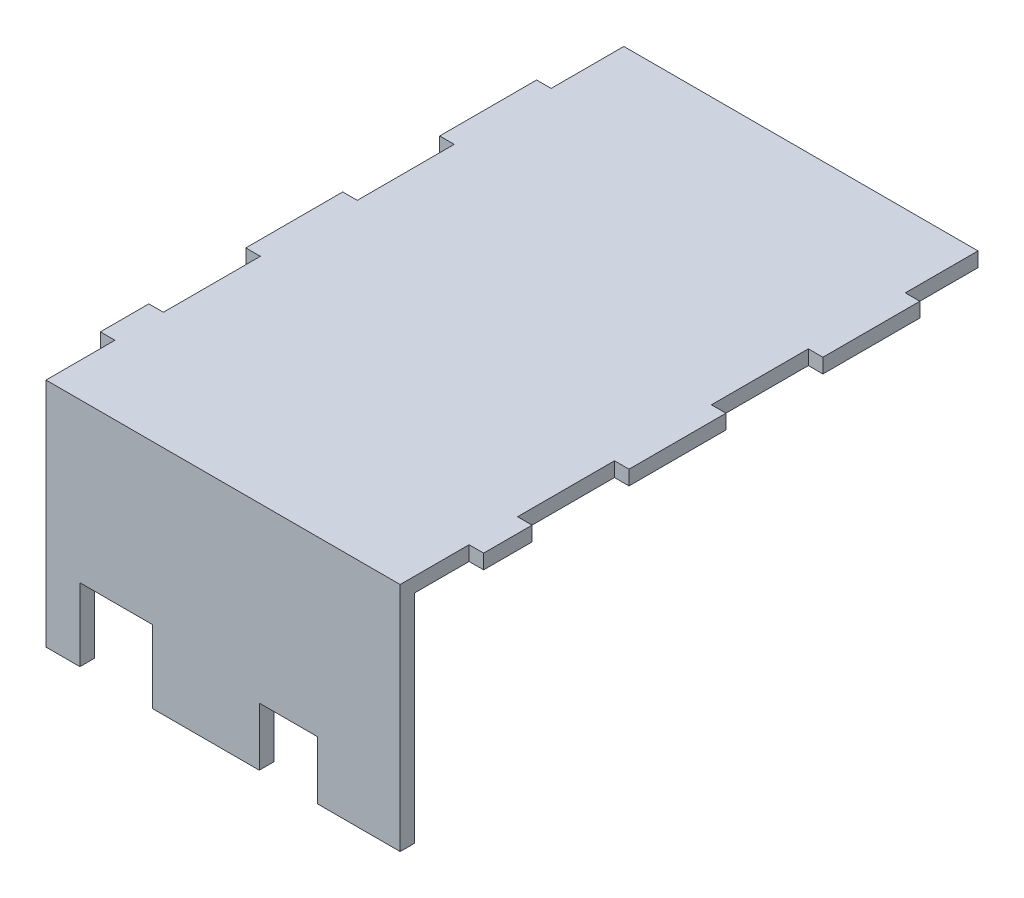
SolidWorks part; units mm, degrees
ref_plane "Front Plane" through (0, 0, 0) normal (0, 0, 1) x (1, 0, 0)
ref_plane "Top Plane" through (0, 0, 0) normal (0, 1, 0) x (1, 0, 0)
ref_plane "Right Plane" through (0, 0, 0) normal (1, 0, 0) x (0, 0, -1)
sketch "Croquis1" plane through (0, 0, 0) normal (0, 1, 0) x (1, 0, 0)
  line L0 (-44.0044, 25.1156) -> (29.0656, 25.1156)
  line L1 (29.0656, 25.1156) -> (29.0656, 10.1156)
  line L3 (-44.0044, -69.8844) -> (-44.0044, -49.8844)
  line L4 (-44.0044, 25.1156) -> (-44.0044, 10.1156)
  line L5 (-44.0044, 10.1156) -> (-47.0044, 10.1156)
  line L6 (-47.0044, 10.1156) -> (-47.0044, -9.8844)
  line L7 (-47.0044, -9.8844) -> (-44.0044, -9.8844)
  line L8 (-44.0044, -9.8844) -> (-44.0044, -29.8844)
  line L9 (-44.0044, -29.8844) -> (-47.0044, -29.8844)
  line L10 (-47.0044, -29.8844) -> (-47.0044, -49.8844)
  line L11 (-47.0044, -49.8844) -> (-44.0044, -49.8844)
  line L12 (-44.0044, -49.8844) -> (-44.0044, -69.8844)
  line L13 (-44.0044, -69.8844) -> (-47.0044, -69.8844)
  line L14 (-47.0044, -69.8844) -> (-47.0044, -79.8844)
  line L15 (-47.0044, -79.8844) -> (-44.0044, -79.8844)
  line L17 (-44.0044, -94.1044) -> (29.0656, -94.1044)
  line L18 (29.0656, -94.1044) -> (29.0656, -82.8844)
  line L19 (-44.0044, -79.8844) -> (-44.0044, -94.1044)
  line L20 (29.0656, -9.8844) -> (29.0656, -29.8844)
  line L21 (32.0656, -79.8844) -> (29.0656, -79.8844)
  line L22 (32.0656, -69.8844) -> (32.0656, -79.8844)
  line L23 (29.0656, -69.8844) -> (32.0656, -69.8844)
  line L24 (32.0656, -49.8844) -> (29.0656, -49.8844)
  line L25 (32.0656, -29.8844) -> (32.0656, -49.8844)
  line L26 (29.0656, -29.8844) -> (32.0656, -29.8844)
  line L27 (32.0656, -9.8844) -> (29.0656, -9.8844)
  line L28 (32.0656, 10.1156) -> (32.0656, -9.8844)
  line L29 (29.0656, 10.1156) -> (32.0656, 10.1156)
  line L30 (29.0656, -49.8844) -> (29.0656, -69.8844)
  line L31 (29.0656, -79.8844) -> (29.0656, -82.8844)
  line L32 (-44.0044, -29.8844) -> (-44.0044, -9.8844)
  line L33 (-44.0044, 10.1156) -> (-44.0044, 25.1156)
  point P3 (0, 0)
  dimension "D10" = 14.22
  dimension "D1" = 73.07
  dimension "D2" = 108
  dimension "D3" = 15
  dimension "D4" = 3
  dimension "D5" = 20
  dimension "D6" = 20
  dimension "D7" = 20
  dimension "D8" = 20
  dimension "D9" = 10
extrude "Saliente-Extruir1" add sketch "Croquis1" along normal blind 3 contours L31 L21 L22 L23 L30 L24 L25 L26 L20 L27 L28 L29 L1 L0 L4 L5 L6 L7 L8 L9 L10 L11 L3 L13 L14 L15 L19 L17 L18
sketch "Croquis2" plane through (0, 3, 0) normal (0, 1, 0) x (1, 0, 0)
  line L0 (-44.0044, -94.1044) -> (-44.0044, -91.1044)
  line L1 (-44.0044, -79.8844) -> (-44.0044, -94.1044) construction
  line L2 (-44.0044, -91.1044) -> (29.0656, -91.1044)
  line L3 (29.0656, -79.8844) -> (29.0656, -94.1044) construction
  line L4 (29.0656, -91.1044) -> (29.0656, -94.1044)
  line L5 (29.0656, -94.1044) -> (-44.0044, -94.1044)
  dimension "D1" = 3
extrude "Saliente-Extruir2" add sketch "Croquis2" against normal blind 47.72
sketch "Croquis3" plane through (0, 0, 94.1044) normal (0, 0, 1) x (1, 0, 0)
  line L1 (-44.0044, -44.72) -> (29.0656, -44.72) construction
  line L2 (-37.0044, -44.72) -> (-37.0044, -29.72)
  line L3 (-37.0044, -29.72) -> (-22.0044, -29.72)
  line L4 (-22.0044, -29.72) -> (-22.0044, -44.72)
  line L5 (-0.3989, -44.72) -> (-0.0044, -44.72)
  line L6 (-0.0044, -44.72) -> (-0.0044, -32.72)
  line L7 (-0.0044, -32.72) -> (11.9956, -32.72)
  line L8 (11.9956, -32.72) -> (11.9956, -44.72)
  line L9 (-37.0044, -44.72) -> (-22.0044, -44.72)
  line L10 (-0.3989, -44.72) -> (11.9956, -44.72)
  line M2 (-44.0044, -44.72) -> (29.0656, -44.72)
  dimension "D2" = 15
  dimension "D3" = 15
  dimension "D4" = 22
  dimension "D5" = 12
  dimension "D6" = 12
extrude "Cortar-Extruir1" cut sketch "Croquis3" against normal blind 47.72 contours L4 L3 L2 M2 | L8 L7 L6 M2
